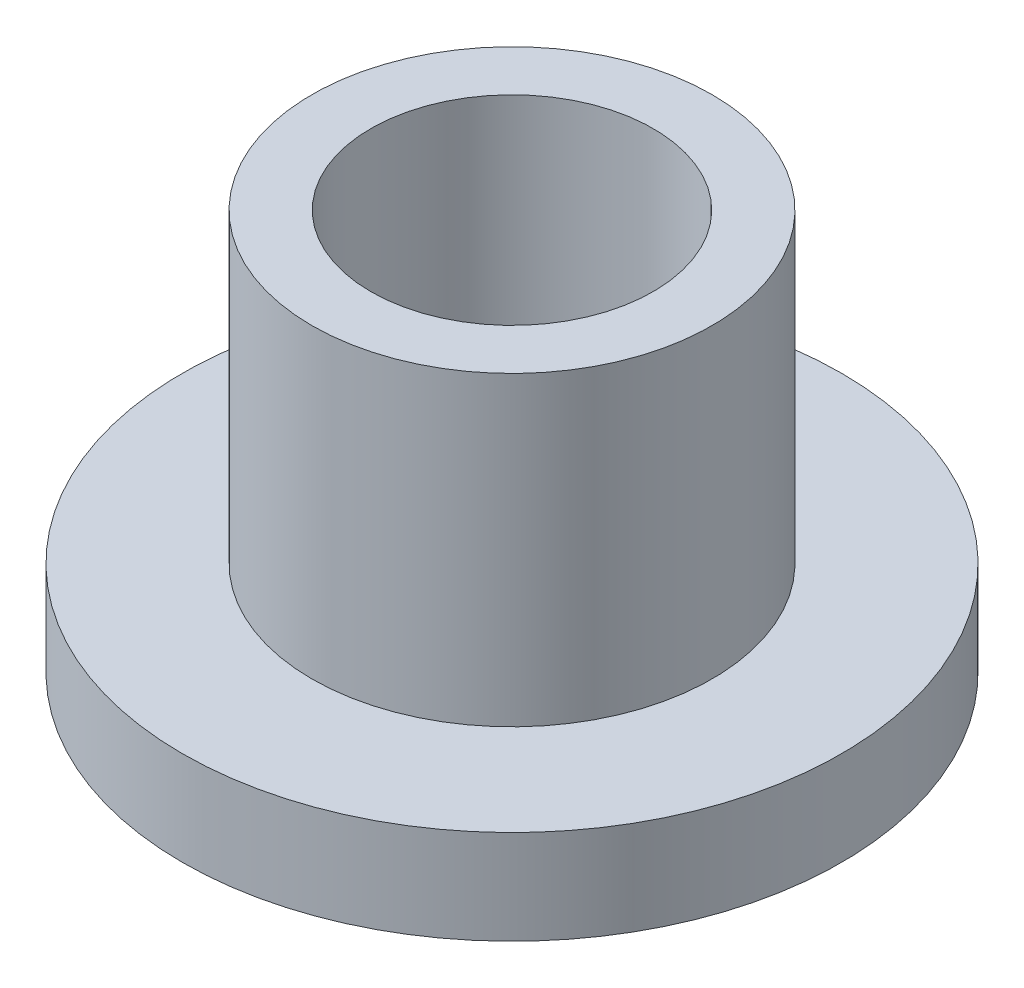
SolidWorks part; units mm, degrees
ref_plane "前视基准面" through (0, 0, 0) normal (0, 0, 1) x (1, 0, 0)
ref_plane "上视基准面" through (0, 0, 0) normal (0, 1, 0) x (1, 0, 0)
ref_plane "右视基准面" through (0, 0, 0) normal (1, 0, 0) x (0, 0, -1)
sketch "草图1" plane through (0, 0, 0) normal (0, 1, 0) x (1, 0, 0)
  circle A0 centre (0, 0) radius 7
  dimension "D1" = 14
extrude "凸台-拉伸1" add sketch "草图1" along normal blind 2
sketch "草图2" plane through (0, 2, 0) normal (0, 1, 0) x (1, 0, 0)
  circle A0 centre (0, 0) radius 4.25
  dimension "D1" = 8.5
extrude "凸台-拉伸2" add sketch "草图2" along normal blind 6.5
sketch "草图3" plane through (0, 8.5, 0) normal (0, 1, 0) x (1, 0, 0)
  circle A0 centre (0, 0) radius 3
  dimension "D1" = 6
extrude "切除-拉伸1" cut sketch "草图3" against normal up to next
